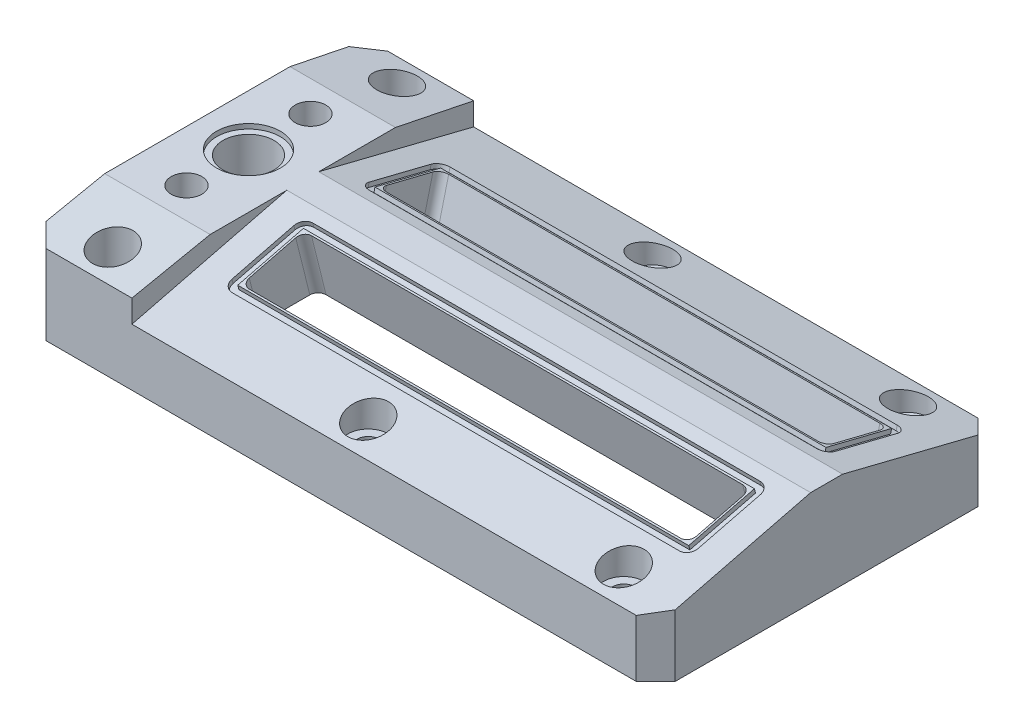
SolidWorks part; units mm, degrees
ref_plane "Front Plane" through (0, 0, 0) normal (0, 0, 1) x (1, 0, 0)
ref_plane "Top Plane" through (0, 0, 0) normal (0, 1, 0) x (1, 0, 0)
ref_plane "Right Plane" through (0, 0, 0) normal (1, 0, 0) x (0, 0, -1)
sketch "Sketch1" plane through (0, 0, 0) normal (0, 1, 0) x (1, 0, 0)
  line L1 (0, 0) -> (197, 0)
  line L2 (0, 0) -> (0, 107)
  line L3 (0, 107) -> (197, 107)
  line L4 (197, 0) -> (197, 107)
  dimension "D1" = 197
  dimension "D2" = 107
extrude "Boss-Extrude1" add sketch "Sketch1" along normal blind 30
ref_plane "Left" through (197, 0, 0) normal (1, 0, 0) x (0, 0, -1)
ref_plane "Bot" through (0, 30, 0) normal (0, 1, 0) x (1, 0, 0)
sketch "Sketch3" plane through (0, 30, 0) normal (0, 1, 0) x (1, 0, 0)
  line L23 (0, 0) -> (6.1, 0)
  line L24 (0, 0) -> (197, 0) construction
  line L25 (6.1, 0) -> (0, 6.1)
  line L26 (0, 107) -> (0, 0) construction
  line L27 (0, 6.1) -> (0, 0)
  line L28 (0, 107) -> (6.1, 107)
  line L29 (197, 107) -> (0, 107) construction
  line L30 (6.1, 107) -> (0, 100.9)
  line L31 (0, 100.9) -> (0, 107)
  line L32 (98.5, 0) -> (98.5, 107) construction
  line L33 (197, 100.9) -> (197, 107)
  line L34 (190.9, 107) -> (197, 100.9)
  line L35 (197, 107) -> (190.9, 107)
  line L36 (197, 6.1) -> (197, 0)
  line L37 (190.9, 0) -> (197, 6.1)
  line L38 (197, 0) -> (190.9, 0)
  dimension "D1" = 6.1
  dimension "D2" = 6.1
  dimension "D3" = 6.1
extrude "Cut-Extrude1" cut sketch "Sketch3" against normal through all
sketch "Sketch4" plane through (0, 0, 0) normal (0, 1, 0) x (1, 0, 0)
  line L1 (7.5, 31) -> (189.5, 31)
  line L2 (7.5, 31) -> (7.5, 76)
  line L3 (7.5, 76) -> (189.5, 76)
  line L4 (189.5, 31) -> (189.5, 76)
  line L6 (0, 100.9) -> (0, 6.1) construction
  line L7 (190.9, 107) -> (6.1, 107) construction
  point P6 (0, 53.5)
  point P7 (7.5, 53.5)
  point P8 (98.5, 76)
  point P11 (98.5, 107)
  dimension "D1" = 182
  dimension "D3" = 45
extrude "Cut-Extrude2" cut sketch "Sketch4" along normal blind 10
sketch "Sketch5" plane through (197, 0, 0) normal (1, 0, 0) x (0, 0, -1)
  line L0 (58.5, 30) -> (107, 17.9076)
  line L1 (6.1, 30) -> (100.9, 30) construction
  line L2 (107, 17.9076) -> (107, 30)
  line L3 (107, 30) -> (58.5, 30)
  line L4 (107, 30) -> (107, 0) construction
  line L5 (0, 17.9076) -> (0, 30)
  line L7 (0, 30) -> (48.5, 30)
  line L8 (48.5, 30) -> (0, 17.9076)
  line L9 (0, 30) -> (0, 0) construction
  line L11 (6.1, 30) -> (0, 30) construction
  point P4 (0, 15)
  point P9 (0, 17.7564)
  point P18 (0, 0)
  point P19 (0, 26.1412)
  dimension "D1" = 14
  dimension "D2" = 48.5
  dimension "D3" = 48.5
  dimension "D4" = 14
extrude "Cut-Extrude3" cut sketch "Sketch5" against normal blind 164
ref_plane "Plane3" through (0, 41.9763, -10.4659) normal (0, 0.9703, -0.2419) x (1, 0, 0)
ref_plane "Plane9" through (0, 16.8595, 4.2036) normal (0, 0.9703, 0.2419) x (1, 0, 0)
sketch "Sketch19" plane through (0, 16.8595, 4.2036) normal (0, 0.9703, 0.2419) x (1, 0, 0)
  line L0 (0, 105.1605) -> (0, 13.1765) construction
  line L1 (45, 24.3322) -> (185, 24.3322)
  line L2 (42, 27.3322) -> (42, 47.3322)
  line L3 (45, 50.3322) -> (185, 50.3322)
  line L4 (188, 27.3322) -> (188, 47.3322)
  line L5 (33, 4.3322) -> (190.9, 4.3322) construction
  line L7 (44.4, 26.7322) -> (185.6, 26.7322)
  line L8 (44.4, 26.7322) -> (44.4, 47.9322)
  line L9 (44.4, 47.9322) -> (185.6, 47.9322)
  line L10 (185.6, 26.7322) -> (185.6, 47.9322)
  arc A0 (185, 24.3322) -> (188, 27.3322) centre (185, 27.3322) ccw
  arc A1 (185, 50.3322) -> (188, 47.3322) centre (185, 47.3322) cw
  arc A2 (42, 47.3322) -> (45, 50.3322) centre (45, 47.3322) cw
  arc A3 (45, 24.3322) -> (42, 27.3322) centre (45, 27.3322) cw
  point P14 (188, 24.3322)
  point P19 (42, 50.3322)
  point P22 (42, 24.3322)
  dimension "D9" = 3
  dimension "D1" = 26
  dimension "D2" = 146
  dimension "D3" = 42
  dimension "D4" = 20
  dimension "D5" = 2.4
  dimension "D6" = 2.4
  dimension "D7" = 2.4
  dimension "D8" = 2.4
extrude "Cut-Extrude15" cut sketch "Sketch19" against normal blind 1.4
sketch "Sketch6" plane through (0, 41.9763, -10.4659) normal (0, 0.9703, -0.2419) x (1, 0, 0)
  line L1 (45, 79.4894) -> (185, 79.4894)
  line L2 (42, 76.4894) -> (42, 56.4894)
  line L3 (45, 53.4894) -> (185, 53.4894)
  line L4 (188, 76.4894) -> (188, 56.4894)
  line L5 (44.4, 55.8894) -> (185.6, 55.8894)
  line L6 (44.4, 55.8894) -> (44.4, 77.0894)
  line L7 (44.4, 77.0894) -> (185.6, 77.0894)
  line L8 (185.6, 55.8894) -> (185.6, 77.0894)
  line L12 (0, 90.6452) -> (0, -1.3389) construction
  line L13 (33, 99.4894) -> (190.9, 99.4894) construction
  arc A0 (185, 79.4894) -> (188, 76.4894) centre (185, 76.4894) cw
  arc A1 (185, 53.4894) -> (188, 56.4894) centre (185, 56.4894) ccw
  arc A2 (42, 56.4894) -> (45, 53.4894) centre (45, 56.4894) ccw
  arc A3 (45, 79.4894) -> (42, 76.4894) centre (45, 76.4894) ccw
  dimension "D1" = 3
  dimension "D2" = 146
  dimension "D3" = 26
  dimension "D4" = 42
  dimension "D5" = 46
  dimension "D6" = 2.4
  dimension "D7" = 2.4
  dimension "D8" = 2.4
  dimension "D9" = 2.4
extrude "Cut-Extrude4" cut sketch "Sketch6" against normal blind 1.4
sketch "Sketch7" plane through (0, 0, 0) normal (1, 0, 0) x (0, 0, -1)
  line L2 (100.9, 30) -> (6.1, 30) construction
  line L3 (107, 30) -> (107, 25)
  line L5 (107, 25) -> (82.5051, 30)
  line L6 (107, 30) -> (82.5051, 30)
  line L7 (0, 25) -> (0, 30)
  line L8 (0, 30) -> (0, 0) construction
  line L9 (0, 30) -> (24.4949, 30)
  line L10 (24.4949, 30) -> (0, 25)
  line L11 (0, 0) -> (0, 30) construction
  line L12 (107, 0) -> (107, 30) construction
  point P3 (101.6787, 30)
  point P8 (0, 18.7049)
  dimension "D1" = 25
  dimension "D2" = 5
  dimension "D3" = 5
  dimension "D4" = 25
extrude "Cut-Extrude5" cut sketch "Sketch7" along normal up to surface (33 mm away) up to face at (33, 25.9692, -90.8333)
sketch "Sketch9" plane through (0, 30, 0) normal (0, 1, 0) x (1, 0, 0)
  line L0 (0, 82.5051) -> (0, 24.4949) construction
  circle A0 centre (16, 53.5) radius 8
  point P6 (0, 53.5)
  dimension "D1" = 16
  dimension "D2" = 16
extrude "Cut-Extrude6" cut sketch "Sketch9" against normal blind 171
sketch "Sketch10" plane through (0, 30, 0) normal (0, 1, 0) x (1, 0, 0)
  circle A0 centre (16, 53.5) radius 10
  dimension "D1" = 20
extrude "Cut-Extrude7" cut sketch "Sketch10" against normal blind 1.5
sketch "Sketch11" plane through (0, 30, 0) normal (0, 1, 0) x (1, 0, 0)
  line L0 (33, 82.5051) -> (0, 82.5051) construction
  line L1 (16, 61.5) -> (16, 53.5) construction
  line L2 (33, 24.4949) -> (0, 24.4949) construction
  circle A0 centre (16, 72.9051) radius 4.8
  circle A1 centre (16, 34.0949) radius 4.8
  circle A6 centre (16, 53.5) radius 8 construction
  dimension "D1" = 9.6
  dimension "D3" = 9.6
  dimension "D2" = 9.6
  dimension "D4" = 9.6
extrude "Cut-Extrude8" cut sketch "Sketch11" against normal blind 12.5
sketch "Sketch12" plane through (0, 30, 0) normal (0, 1, 0) x (1, 0, 0)
  line L0 (0, 82.5051) -> (0, 100.9) construction
  line L2 (33, 107) -> (6.1, 107) construction
  line L3 (33, 0) -> (6.1, 0) construction
  circle A0 centre (18, 98) radius 6.35
  circle A1 centre (98, 9) radius 6.35
  circle A2 centre (178, 9) radius 6.35
  circle A3 centre (18, 9) radius 6.35
  circle A4 centre (98, 98) radius 6.35
  circle A5 centre (178, 98) radius 6.35
  dimension "D1" = 12.7
  dimension "D2" = 12.7
  dimension "D3" = 12.7
  dimension "D4" = 12.7
  dimension "D5" = 12.7
  dimension "D6" = 12.7
  dimension "D7" = 80
  dimension "D8" = 18
  dimension "D9" = 80
  dimension "D10" = 9
  dimension "D11" = 9
extrude "Cut-Extrude9" cut sketch "Sketch12" against normal blind 17
ref_plane "Plane8" through (0, 24, 4.899) normal (0, 0.9798, 0.2) x (1, 0, 0)
sketch "Sketch16" plane through (0, 41.9763, -10.4659) normal (0, 0.9703, -0.2419) x (1, 0, 0)
  line L0 (44.4, 77.0894) -> (44.4, 55.8894) construction
  line L1 (47.5, 56.4894) -> (182.5, 56.4894)
  line L2 (45, 58.9894) -> (45, 73.9894)
  line L3 (47.5, 76.4894) -> (182.5, 76.4894)
  line L4 (185, 58.9894) -> (185, 73.9894)
  line L5 (44.4, 55.8894) -> (185.6, 55.8894) construction
  line L6 (185.6, 77.0894) -> (44.4, 77.0894) construction
  line L7 (185.6, 55.8894) -> (185.6, 77.0894) construction
  arc A0 (182.5, 56.4894) -> (185, 58.9894) centre (182.5, 58.9894) ccw
  arc A1 (182.5, 76.4894) -> (185, 73.9894) centre (182.5, 73.9894) cw
  arc A2 (45, 73.9894) -> (47.5, 76.4894) centre (47.5, 73.9894) cw
  arc A3 (47.5, 56.4894) -> (45, 58.9894) centre (47.5, 58.9894) cw
  dimension "D5" = 2.5
  dimension "D1" = 0.6
  dimension "D2" = 0.6
  dimension "D3" = 0.6
  dimension "D4" = 0.6
extrude "Cut-Extrude13" cut sketch "Sketch16" against normal up to surface (18.8708 mm away)
sketch "Sketch17" plane through (0, 30, 0) normal (0, 1, 0) x (1, 0, 0)
  circle A0 centre (18, 9) radius 3.5
  circle A1 centre (18, 98) radius 3.5
  circle A2 centre (98, 98) radius 3.5
  circle A3 centre (178, 98) radius 3.5
  circle A4 centre (178, 9) radius 3.5
  circle A5 centre (98, 9) radius 3.5
  dimension "D1" = 7
  dimension "D2" = 7
  dimension "D3" = 7
  dimension "D4" = 7
  dimension "D5" = 7
  dimension "D6" = 7
extrude "Cut-Extrude14" cut sketch "Sketch17" against normal through all
sketch "Sketch20" plane through (0, 16.8595, 4.2036) normal (0, 0.9703, 0.2419) x (1, 0, 0)
  line L0 (44.4, 47.9322) -> (44.4, 26.7322) construction
  line L1 (47.5, 27.3322) -> (182.5, 27.3322)
  line L2 (45, 29.8322) -> (45, 44.8322)
  line L3 (47.5, 47.3322) -> (182.5, 47.3322)
  line L4 (185, 29.8322) -> (185, 44.8322)
  line L5 (185.6, 47.9322) -> (44.4, 47.9322) construction
  line L6 (44.4, 26.7322) -> (185.6, 26.7322) construction
  line L7 (185.6, 26.7322) -> (185.6, 47.9322) construction
  arc A0 (182.5, 47.3322) -> (185, 44.8322) centre (182.5, 44.8322) cw
  arc A1 (182.5, 27.3322) -> (185, 29.8322) centre (182.5, 29.8322) ccw
  arc A2 (45, 44.8322) -> (47.5, 47.3322) centre (47.5, 44.8322) cw
  arc A3 (47.5, 27.3322) -> (45, 29.8322) centre (47.5, 29.8322) cw
  dimension "D5" = 2.5
  dimension "D1" = 0.6
  dimension "D2" = 0.6
  dimension "D3" = 0.6
  dimension "D4" = 0.6
extrude "Cut-Extrude16" cut sketch "Sketch20" against normal up to surface (18.8708 mm away)
